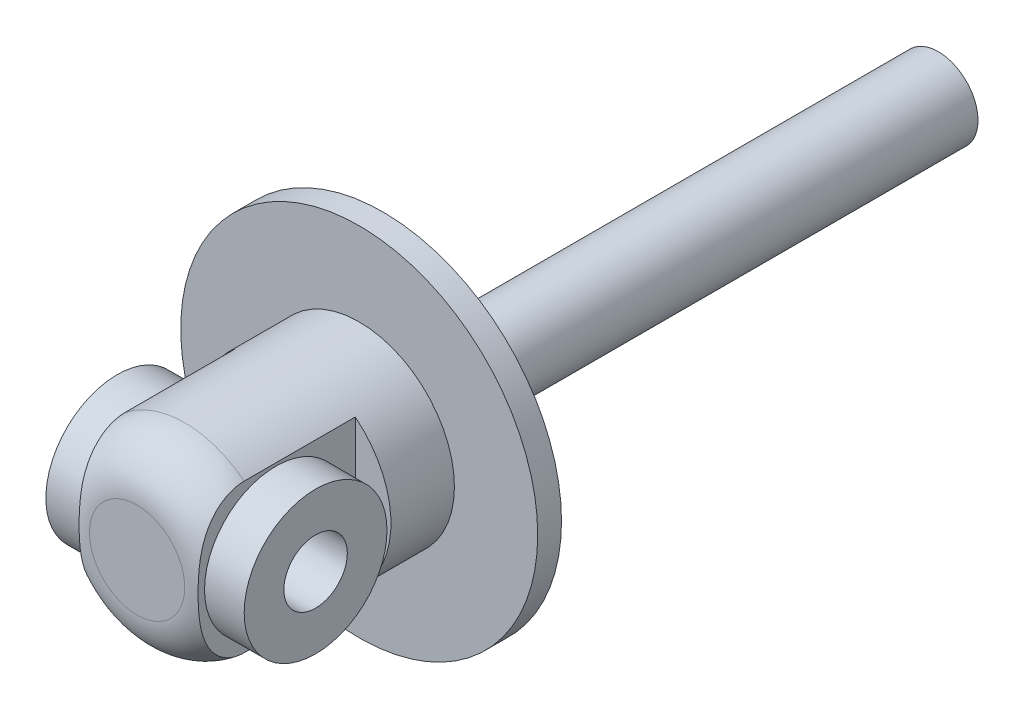
SolidWorks part; units mm, degrees
ref_plane "Front Plane" through (0, 0, 0) normal (1, 0, 0) x (0, 1, 0)
ref_plane "Top Plane" through (0, 0, 0) normal (0, 0, 1) x (0, 1, 0)
ref_plane "Right Plane" through (0, 0, 0) normal (0, 1, 0) x (-1, 0, 0)
sketch "Sketch1" plane through (0, 0, 0) normal (0, 0, 1) x (0, 1, 0)
  circle A0 centre (0, 0) radius 5
  dimension "D1" = 10
extrude "Boss-Extrude1" add sketch "Sketch1" along normal blind 70
sketch "Sketch2" plane through (0, 0, 70) normal (0, 0, 1) x (1, 0, 0)
  circle A0 centre (0, 0) radius 22.5
  dimension "D1" = 45
extrude "Boss-Extrude2" add sketch "Sketch2" along normal blind 3
sketch "Sketch3" plane through (0, 0, 73) normal (0, 0, 1) x (1, 0, 0)
  circle A0 centre (0, 0) radius 12
  dimension "D1" = 24
extrude "Boss-Extrude3" add sketch "Sketch3" along normal blind 28
fillet "Fillet1" radius 6 1 edges at (12, 0, 101)
sketch "Sketch4" plane through (0, 0, 0) normal (0, 1, 0) x (-1, 0, 0)
  line L0 (0, 101) -> (0, 73.0556) construction
  line L1 (6, 101) -> (-6, 101) construction
  line L2 (17.5, 81) -> (7.5, 81)
  line L3 (-17.5, 101) -> (-7.5, 101)
  line L4 (-17.5, 101) -> (-17.5, 81)
  line L5 (-17.5, 81) -> (-7.5, 81)
  line L6 (-7.5, 101) -> (-7.5, 81)
  line L7 (7.5, 101) -> (7.5, 81)
  line L8 (17.5, 101) -> (7.5, 101)
  line L9 (17.5, 101) -> (17.5, 81)
  dimension "D1" = 20
  dimension "D2" = 7.5
  dimension "D3" = 10
extrude "Cut-Extrude1" cut sketch "Sketch4" against normal mid plane 28
sketch "Sketch5" plane through (7.5, 0, 0) normal (1, 0, 0) x (0, 1, 0)
  line L0 (0, 101) -> (0, 81) construction
  line L1 (6, 101) -> (-6, 101) construction
  line L2 (-9.3675, 81) -> (9.3675, 81) construction
  circle A0 centre (0, 91) radius 4
  dimension "D2" = 8
  dimension "D1" = 10
extrude "Cut-Extrude2" cut sketch "Sketch5" against normal through all
sketch "Sketch6" plane through (0, 0, 0) normal (1, 0, 0) x (0, 1, 0)
  circle A0 centre (0, 91) radius 9
  dimension "D1" = 18
extrude "Boss-Extrude4" add sketch "Sketch6" along normal mid plane 25
sketch "Sketch7" plane through (-12.5, 0, 0) normal (-1, 0, 0) x (0, -1, 0)
  circle A0 centre (0, 91) radius 4
  dimension "D1" = 8
extrude "Cut-Extrude3" cut sketch "Sketch7" against normal through all
